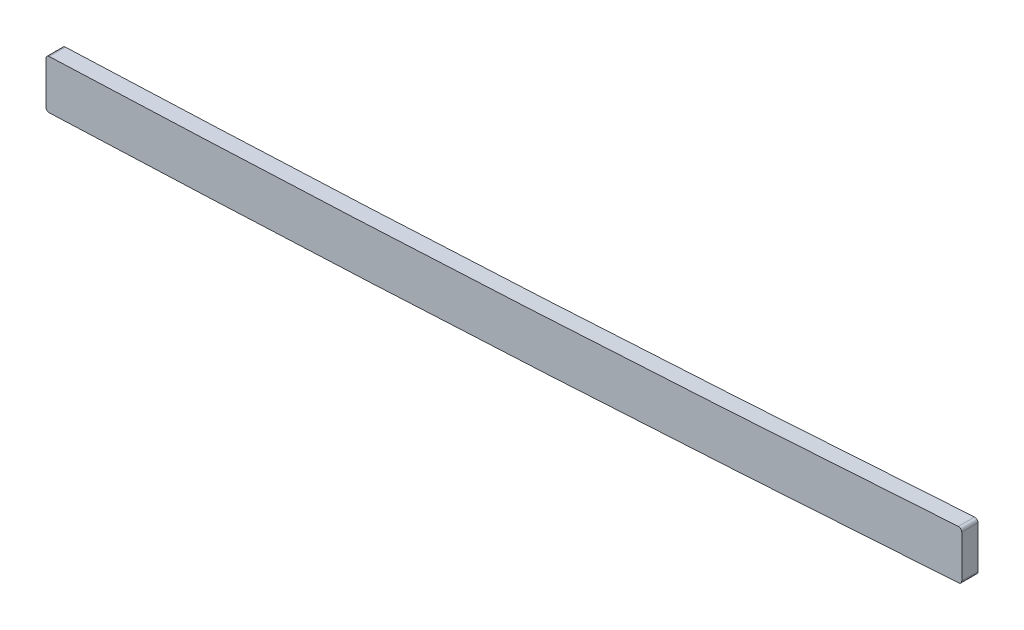
SolidWorks part; units mm, degrees
ref_plane "Front Plane" through (0, 0, 0) normal (0, 0, 1) x (1, 0, 0)
ref_plane "Top Plane" through (0, 0, 0) normal (0, 1, 0) x (1, 0, 0)
ref_plane "Right Plane" through (0, 0, 0) normal (1, 0, 0) x (0, 0, -1)
sketch "Sketch1" plane through (0, 0, 0) normal (0, 0, 1) x (1, 0, 0)
  line L0 (1046.2855, 53.4707) -> (499.61, 53.4707) construction
  line L1 (55, 0) -> (-55, 0) construction
  line L2 (1046.2855, -53.4707) -> (499.61, -53.4707)
  line L3 (1046.2855, -34.4207) -> (499.61, -34.4207)
  line L4 (99.06, -18.1493) -> (99.06, -37.7415)
  line L5 (2669.54, 9.5231) -> (2669.54, -9.569)
  line L6 (2311.4, -9.2457) -> (2311.4, -28.3104)
  spline S0 degree 5 poles (2699.7923, 7.5245) (2639.6368, 11.6572) (2579.4813, 15.4358) (2518.4981, 19.1485) (2436.3555, 23.2524) (2354.213, 26.6315) (2332.5703, 27.481) (2156.2686, 34.3778) (1979.9669, 41.6286) (1824.1143, 52.7713) (1636.9286, 53.5796) (1449.7429, 53.454) (1418.0067, 53.4707) (1324.8993, 53.4707) (1231.7919, 53.4707) (1170.4413, 53.4707) (1108.7841, 53.4707) (1047.1269, 53.4707) (1046.8464, 53.4707) (1046.5659, 53.4707) (1046.2855, 53.4707) knots 100.654805 100.654805 100.654805 100.654805 100.654805 100.654805 130.927897 130.927897 130.927897 141.337055 141.337055 141.337055 218.101815 218.101815 218.101815 233.772059 233.772059 233.772059 264.077723 264.077723 264.077723 264.216209 264.216209 264.216209 264.216209 264.216209 264.216209 weights 1 1 1 1 1 1 1 1 1 1 1 1 1 1 1 1 1 1 1 1 1 construction
  spline S1 degree 5 poles (499.61, 53.4707) (492.1368, 53.4707) (484.7543, 53.4707) (477.443, 53.4707) (448.5166, 53.4707) (419.5901, 53.4707) (398.3681, 53.4707) (355.6475, 53.4707) (312.927, 53.4707) (289.2351, 53.4703) (265.365, 53.4707) (241.4948, 53.4707) (241.4716, 53.4707) (241.4484, 53.4707) (241.4251, 53.4707) knots 19.90683 19.90683 19.90683 19.90683 19.90683 19.90683 23.637897 23.637897 23.637897 34.276546 34.276546 34.276546 46.401341 46.401341 46.401341 46.413154 46.413154 46.413154 46.413154 46.413154 46.413154 weights 1 1 1 1 1 1 1 1 1 1 1 1 1 1 1 construction
  spline S2 degree 5 poles (241.4251, 53.4707) (224.2869, 53.4707) (207.1495, 53.4673) (190.2039, 52.6866) (151.6561, 49.0319) (113.1083, 41.5037) (91.9499, 36.3426) (71.313, 30.9696) (50.6762, 24.7565) knots 0 0 0 0 0 0 8.713816 8.713816 8.713816 19.90683 19.90683 19.90683 19.90683 19.90683 19.90683 weights 1 1 1 1 1 1 1 1 1 construction
  spline S3 degree 5 poles (241.4251, -53.4707) (224.2869, -53.4707) (207.1495, -53.4673) (190.2039, -52.6866) (151.6561, -49.0319) (113.1083, -41.5037) (91.9499, -36.3426) (71.313, -30.9696) (50.6762, -24.7565) knots 0 0 0 0 0 0 8.713816 8.713816 8.713816 19.90683 19.90683 19.90683 19.90683 19.90683 19.90683 weights 1 1 1 1 1 1 1 1 1
  spline S4 degree 5 poles (499.61, -53.4707) (492.1368, -53.4707) (484.7543, -53.4707) (477.443, -53.4707) (448.5166, -53.4707) (419.5901, -53.4707) (398.3681, -53.4707) (355.6475, -53.4707) (312.927, -53.4707) (289.2351, -53.4703) (265.365, -53.4707) (241.4948, -53.4707) (241.4716, -53.4707) (241.4484, -53.4707) (241.4251, -53.4707) knots 19.90683 19.90683 19.90683 19.90683 19.90683 19.90683 23.637897 23.637897 23.637897 34.276546 34.276546 34.276546 46.401341 46.401341 46.401341 46.413154 46.413154 46.413154 46.413154 46.413154 46.413154 weights 1 1 1 1 1 1 1 1 1 1 1 1 1 1 1
  spline S5 degree 5 poles (2699.7923, -7.5245) (2639.6368, -11.6572) (2579.4813, -15.4358) (2518.4981, -19.1485) (2436.3555, -23.2524) (2354.213, -26.6315) (2332.5703, -27.481) (2156.2686, -34.3778) (1979.9669, -41.6286) (1824.1143, -52.7713) (1636.9286, -53.5796) (1449.7429, -53.454) (1418.0067, -53.4707) (1324.8993, -53.4707) (1231.7919, -53.4707) (1170.4413, -53.4707) (1108.7841, -53.4707) (1047.1269, -53.4707) (1046.8464, -53.4707) (1046.5659, -53.4707) (1046.2855, -53.4707) knots 100.654805 100.654805 100.654805 100.654805 100.654805 100.654805 130.927897 130.927897 130.927897 141.337055 141.337055 141.337055 218.101815 218.101815 218.101815 233.772059 233.772059 233.772059 264.077723 264.077723 264.077723 264.216209 264.216209 264.216209 264.216209 264.216209 264.216209 weights 1 1 1 1 1 1 1 1 1 1 1 1 1 1 1 1 1 1 1 1 1
  spline S6 degree 1 poles (2698.4867, 11.4807) (1046.2855, -34.4207) knots 0 0 1 1 construction
  spline S7 degree 1 poles (499.61, -34.4207) (241.4252, -34.4207) knots 0 0 1 1 construction
  spline S8 degree 1 poles (241.4252, -34.4207) (56.168, -6.5153) knots 0 0 1 1 construction
  spline S9 degree 3 poles (2698.4867, 11.4807) (2691.2474, 10.9833) (2679.1952, 10.1655) (2662.2765, 9.0388) (2635.6663, 7.2925) (2596.8577, 4.8261) (2545.7297, 1.7583) (2494.4053, -1.0986) (2451.533, -3.2666) (2417.1983, -4.8671) (2391.4571, -6.0036) (2365.6347, -7.0869) (2341.0156, -8.0785) (2320.7508, -8.8784) (2303.4475, -9.5581) (2284.7601, -10.2922) (2261.7633, -11.201) (2227.2853, -12.5838) (2184.1756, -14.3661) (2132.4291, -16.6074) (2063.4255, -19.7089) (1977.1749, -23.7005) (1873.7325, -28.1494) (1770.3746, -31.6575) (1667.0857, -33.7931) (1581.0111, -34.3832) (1512.074, -34.4278) (1443.0615, -34.4095) (1356.8009, -34.4244) (1218.7946, -34.4185) (1115.289, -34.4207) (1046.2855, -34.4207) knots 100.654805 100.654805 100.654805 100.654805 102.842388 104.300777 105.766098 110.877392 115.988686 121.09998 126.211274 128.766921 131.322568 133.878215 136.433862 138.55769 139.835514 141.545156 144.100803 146.656449 151.767743 156.879037 161.990331 172.212919 182.435507 192.658094 202.880682 213.10327 218.214564 223.325858 233.548445 243.771033 264.216209 264.216209 264.216209 264.216209
  spline S10 degree 3 poles (499.61, -34.4207) (488.6147, -34.4207) (472.2364, -34.4207) (449.9402, -34.4207) (427.7713, -34.4207) (405.8747, -34.4207) (384.5849, -34.4207) (368.9002, -34.4207) (353.3766, -34.4207) (332.6085, -34.4207) (306.2878, -34.4206) (274.0235, -34.4205) (252.271, -34.4207) (241.4252, -34.4207) knots 19.90683 19.90683 19.90683 19.90683 23.22012 24.876765 26.533411 29.846701 31.503346 33.159992 34.816637 36.473282 39.786573 43.099863 46.413154 46.413154 46.413154 46.413154
  spline S11 degree 3 poles (241.4252, -34.4207) (239.3949, -34.4207) (235.3223, -34.4205) (227.2744, -34.3987) (217.3194, -34.2975) (205.5307, -33.9764) (189.9633, -33.2126) (170.697, -31.5435) (147.5333, -28.3144) (125.4828, -24.2021) (107.4399, -20.1965) (92.2061, -16.4882) (75.9505, -12.2555) (63.6202, -8.7589) (56.168, -6.5153) knots 0 0 0 0 0.622088 1.244177 2.488354 3.732531 4.976707 7.465061 9.953415 12.441768 14.558235 15.802412 17.418476 19.90683 19.90683 19.90683 19.90683
  point P2 (0, 0)
  dimension "D1" = 50.6762
  dimension "D3" = 99.06
  dimension "D4" = 2669.54
  dimension "D5" = 2311.4
  dimension "D2" = 19.05
extrude "Boss-Extrude1" add sketch "Sketch1" along normal mid plane 6.35 contours L5 S9 L6 S5
fillet "Fillet1" radius 1.27 4 edges at (2669.54, 9.5231, 0) (2311.4, -9.2457, 0)
